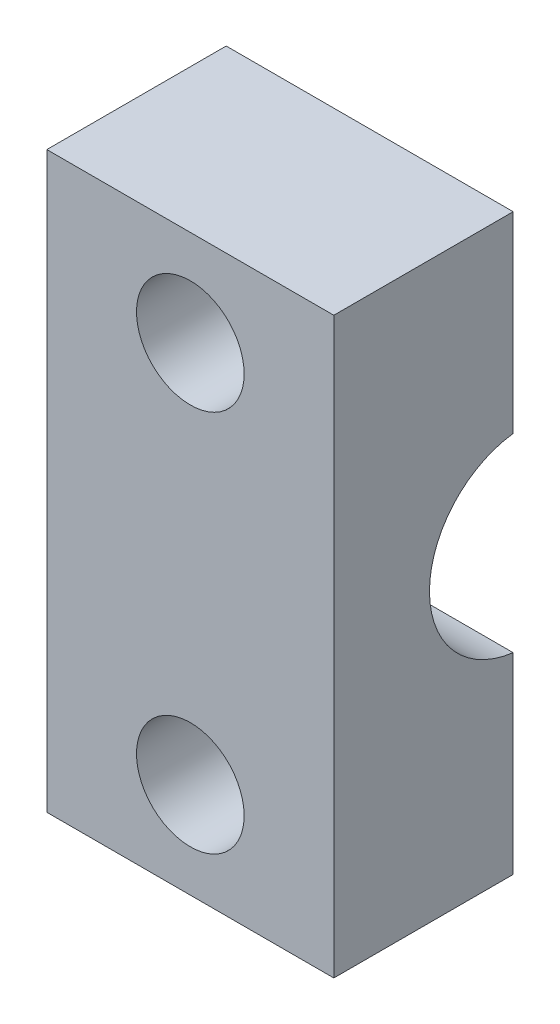
SolidWorks part; units mm, degrees
material "Printed PLA"
ref_plane "Front Plane" through (0, 0, 0) normal (0, 0, 1) x (1, 0, 0)
ref_plane "Top Plane" through (0, 0, 0) normal (0, 1, 0) x (1, 0, 0)
ref_plane "Right Plane" through (0, 0, 0) normal (1, 0, 0) x (0, 0, -1)
sketch "Sketch1" plane through (0, 0, 0) normal (1, 0, 0) x (0, 0, -1)
  line L0 (8, -4) -> (8, -12)
  line L1 (0, 12) -> (8, 12)
  line L2 (0, 12) -> (0, -12)
  line L3 (0, -12) -> (8, -12)
  line L4 (8, 12) -> (8, 4)
  arc A0 (8, 4) -> (8, -4) centre (8, 0) ccw
  dimension "D1" = 8
  dimension "D2" = 24
  dimension "D3" = 8
extrude "Boss-Extrude1" add sketch "Sketch1" along normal blind 12
sketch "Sketch2" plane through (0, 0, 0) normal (0, 0, 1) x (1, 0, 0)
  line L0 (6, -8) -> (6, 8) construction
  line L1 (6, 8) -> (6, 12) construction
  line L2 (12, 12) -> (0, 12) construction
  line L3 (0, 0) -> (6, 0) construction
  line L4 (0, 12) -> (0, -12) construction
  circle A0 centre (6, 8) radius 2.25
  circle A1 centre (6, -8) radius 2.25
  dimension "D2" = 4.5
  dimension "D1" = 16
extrude "Cut-Extrude1" cut sketch "Sketch2" against normal through all
sketch "Sketch3" plane through (0, 0, -8) normal (0, 0, -1) x (-1, 0, 0)
  line L1 (-12, 12) -> (0, 12)
  line L2 (-12, 12) -> (-12, -12)
  line L3 (-12, -12) -> (0, -12)
  line L4 (0, 12) -> (0, -12)
extrude "Cut-Extrude2" cut sketch "Sketch3" against normal blind 0.5
